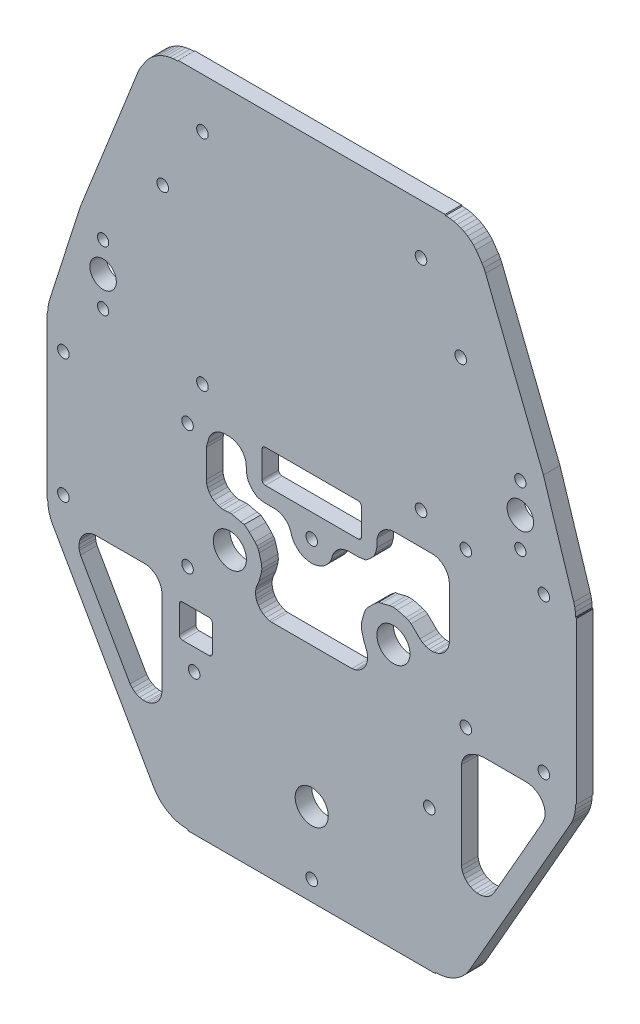
SolidWorks part; units mm, degrees
ref_plane "Plan de face" through (0, 0, 0) normal (1, 0, 0) x (0, 1, 0)
ref_plane "Plan de dessus" through (0, 0, 0) normal (0, 0, 1) x (0, 1, 0)
ref_plane "Plan de droite" through (0, 0, 0) normal (0, 1, 0) x (-1, 0, 0)
sketch "Esquisse1" plane through (0, 0, 0) normal (0, 0, 1) x (0, 1, 0)
  line L0 (0, 0) -> (-150.5414, 0) construction
  line L1 (-100, -80) -> (100, -80)
  line L2 (-100, -80) -> (-100, 80)
  line L3 (-100, 80) -> (100, 80)
  line L5 (-100, -80) -> (100, 80) construction
  line L6 (-100, 80) -> (100, -80) construction
  line L12 (-31, 38.8179) -> (-31, 42.3315) construction
  line L13 (-51, 40) -> (-41, 40)
  line L17 (-51, 40) -> (-51, 30)
  line L18 (-51, 30) -> (-41, 30)
  line L19 (-41, 40) -> (-41, 30)
  line L21 (-31.059, 37.5) -> (-30.571, 37.5) construction
  line L22 (-31, -46.5413) -> (-34.2714, -46.5413) construction
  line L28 (100, 80) -> (100, -80)
  line L30 (2, 15) -> (12, 15)
  line L31 (2, 15) -> (2, -15)
  line L32 (2, -15) -> (12, -15)
  line L33 (12, 15) -> (12, -15)
  circle A0 centre (-75, 0) radius 5
  circle A1 centre (-57.5, 35.5) radius 1.75
  circle A2 centre (-57.5, -35.5) radius 1.75
  circle A3 centre (65, 45) radius 1.75
  circle A4 centre (65, -45) radius 1.75
  circle A5 centre (-31, 37.5) radius 1.75
  circle A6 centre (-31, 75) radius 1.75
  circle A7 centre (6.5, 75) radius 1.75
  circle A8 centre (6.5, 37.5) radius 1.75
  circle A9 centre (-31, -46.5413) radius 1.75
  circle A10 centre (-31, -70.0913) radius 1.75
  circle A11 centre (15.5, -46.5413) radius 1.75
  circle A12 centre (15.5, -70.0913) radius 1.75
  circle A13 centre (-4.9993, 0) radius 1.75
  circle A16 centre (85, 33) radius 1.75
  circle A17 centre (85.0012, -33) radius 1.75
  circle A18 centre (19, 33) radius 1.75
  circle A19 centre (19.0012, -33) radius 1.75
  point P0 (0, 0)
  dimension "D3" = 10
  dimension "D9" = 3.5
  dimension "D10" = 35.5
  dimension "D11" = 17.5
  dimension "D5" = 3.5
  dimension "D6" = 45
  dimension "D7" = 15
  dimension "D16" = 37.5
  dimension "D17" = 37.5
  dimension "D18" = 37.5
  dimension "D19" = 3.5
  dimension "D20" = 3.5
  dimension "D21" = 3.5
  dimension "D22" = 3.5
  dimension "D23" = 10
  dimension "D24" = 5
  dimension "D25" = 3.5
  dimension "D26" = 3.5
  dimension "D27" = 3.5
  dimension "D28" = 3.5
  dimension "D29" = 46.5
  dimension "D30" = 46.5
  dimension "D31" = 23.55
  dimension "D32" = 23.55
  dimension "D35" = 3.5
  dimension "D36" = 3.5
  dimension "D41" = 66
  dimension "D42" = 66
  dimension "D47" = 3.5
  dimension "D48" = 3.5
  dimension "D50" = 66
  dimension "D52" = 33
  dimension "D33" = 14.9988
  dimension "D34" = 3.5
  dimension "D40" = 66
  dimension "D1" = 200
  dimension "D2" = 160
  dimension "D4" = 25
  dimension "D8" = 6.5
  dimension "D12" = 10
  dimension "D13" = 10
  dimension "D14" = 40
  dimension "D15" = 37.5
  dimension "D37" = 15
  dimension "D38" = 15
  dimension "D39" = 10
  dimension "D43" = 102
extrude "Boss.-Extru.1" add sketch "Esquisse1" along normal blind 5
fillet "Congé2" radius 1 8 edges at (-30, -51, 2.5) (-30, -41, 2.5) (-40, -41, 2.5) (-40, -51, 2.5) (15, 2, 2.5) (15, 12, 2.5) (-15, 12, 2.5) (-15, 2, 2.5)
sketch "Esquisse2" plane through (0, 0, 5) normal (0, 0, 1) x (1, 0, 0)
  line L0 (-110, 40) -> (0, 160)
  line L1 (0, 160) -> (110, 40)
  line L2 (110, 40) -> (110, -40)
  line L3 (110, -40) -> (0, -160)
  line L5 (0, -160) -> (-110, -40)
  line L6 (-110, -40) -> (-110, 40)
  line L14 (-573.5804, 598.1671) -> (-698.6982, -488.0825)
  line L15 (-80, 100) -> (-80, -100) construction
  line L16 (80, -100) -> (80, 100) construction
  line L17 (0, 70) -> (0, 33.5097) construction
  line L18 (-698.6982, -488.0825) -> (684.3, -647.3807)
  line L19 (0, 0) -> (-114.7759, 0) construction
  line L20 (684.3, -647.3807) -> (762.9047, 702.4319)
  line L21 (762.9047, 702.4319) -> (-573.5804, 598.1671)
  dimension "D1" = 160
  dimension "D2" = 160
  dimension "D3" = 40
  dimension "D4" = 40
  dimension "D5" = 40
  dimension "D6" = 40
  dimension "D7" = 110
extrude "Enlèv. mat.-Extru.1" cut sketch "Esquisse2" against normal through all
sketch "Esquisse3" plane through (0, 0, 0) normal (0, 0, 1) x (0, 1, 0)
  circle A0 centre (-94.0015, 0.004) radius 1.75
extrude "Trou cuve direction" cut sketch "Esquisse3" along normal through all
sketch "Esquisse4" plane through (0, 0, 5) normal (0, 0, 1) x (1, 0, 0)
  line L0 (-82.024, 47.0385) -> (-45.024, 103.0385)
  line L1 (-45.024, 103.0385) -> (-83.024, 103.0385)
  line L2 (-83.024, 103.0385) -> (-83.024, 47.0385)
  line L3 (-83.024, 47.0385) -> (-82.024, 47.0385)
  line L4 (82.016, 47.0385) -> (45.016, 103.0385)
  line L5 (45.016, 103.0385) -> (83.016, 103.0385)
  line L6 (83.016, 103.0385) -> (83.016, 47.0385)
  line L7 (83.016, 47.0385) -> (82.016, 47.0385)
  circle A0 centre (-63.004, 23.7385) radius 1.7
  circle A1 centre (-63.004, 41.7385) radius 1.7
  circle A2 centre (62.996, 23.7385) radius 1.7
  circle A3 centre (62.996, 41.7385) radius 1.7
  circle A4 centre (-63.004, 32.7385) radius 4
  circle A5 centre (62.996, 32.7385) radius 4
  circle A6 centre (-24.724, -20.2615) radius 5
  circle A7 centre (24.676, -20.2615) radius 5
extrude "Pointe avant, trous berceau et cables" cut sketch "Esquisse4" against normal through all
sketch "Esquisse5" plane through (0, 0, 5) normal (0, 0, 1) x (1, 0, 0)
  line L0 (-80.324, 14.3635) -> (-80.254, 14.1705)
  line L1 (-80.254, 14.1705) -> (-80.076, 14.0675)
  line L2 (-80.076, 14.0675) -> (-79.874, 14.1035)
  line L3 (-79.874, 14.1035) -> (-79.742, 14.2605)
  line L4 (-79.742, 14.2605) -> (-79.662, 15.5635)
  line L5 (-79.662, 15.5635) -> (-79.477, 16.7515)
  line L6 (-79.477, 16.7515) -> (-79.17, 17.9215)
  line L7 (-79.17, 17.9215) -> (-69.975, 46.6925)
  line L8 (-69.975, 46.6925) -> (-52.443, 90.8885)
  line L9 (-52.443, 90.8885) -> (-51.938, 91.9925)
  line L10 (-51.938, 91.9925) -> (-51.322, 93.0375)
  line L11 (-51.322, 93.0375) -> (-49.68, 95.4185)
  line L12 (-49.68, 95.4185) -> (-48.909, 96.2775)
  line L13 (-48.909, 96.2775) -> (-48.056, 97.0555)
  line L14 (-48.056, 97.0555) -> (-47.132, 97.7465)
  line L15 (-47.132, 97.7465) -> (-46.143, 98.3425)
  line L16 (-46.143, 98.3425) -> (-45.101, 98.8385)
  line L17 (-45.101, 98.8385) -> (-44.015, 99.2295)
  line L18 (-44.015, 99.2295) -> (-42.896, 99.5105)
  line L19 (-42.896, 99.5105) -> (-41.754, 99.6815)
  line L20 (-41.754, 99.6815) -> (-40.499, 99.7565)
  line L21 (-40.499, 99.7565) -> (-40.358, 99.8635)
  line L22 (-40.358, 99.8635) -> (-40.302, 100.0305)
  line L23 (-40.302, 100.0305) -> (-40.349, 100.2015)
  line L24 (-40.349, 100.2015) -> (-40.485, 100.3145)
  line L25 (-40.485, 100.3145) -> (-47.056, 100.3385)
  line L26 (-47.056, 100.3385) -> (-47.288, 100.2275)
  line L27 (-47.288, 100.2275) -> (-80.302, 50.2545)
  line L28 (-80.302, 50.2545) -> (-80.324, 14.3635)
  line L29 (-80.324, -72.6885) -> (-80.245, -72.8915)
  line L30 (-80.245, -72.8915) -> (-55.173, -100.2225)
  line L31 (-55.173, -100.2225) -> (-37.575, -100.2615)
  line L32 (-37.575, -100.2615) -> (-37.328, -100.1315)
  line L33 (-37.328, -100.1315) -> (-37.286, -99.8825)
  line L34 (-37.286, -99.8825) -> (-37.476, -99.6785)
  line L35 (-37.476, -99.6785) -> (-39.799, -99.4475)
  line L36 (-39.799, -99.4475) -> (-40.886, -99.1825)
  line L37 (-40.886, -99.1825) -> (-41.942, -98.8155)
  line L38 (-41.942, -98.8155) -> (-42.959, -98.3485)
  line L39 (-42.959, -98.3485) -> (-43.926, -97.7875)
  line L40 (-43.926, -97.7875) -> (-44.835, -97.1365)
  line L41 (-44.835, -97.1365) -> (-45.678, -96.4015)
  line L42 (-45.678, -96.4015) -> (-46.447, -95.5885)
  line L43 (-46.447, -95.5885) -> (-47.135, -94.7065)
  line L44 (-47.135, -94.7065) -> (-47.739, -93.7575)
  line L45 (-47.739, -93.7575) -> (-78.18, -40.4485)
  line L46 (-78.18, -40.4485) -> (-78.73, -39.3585)
  line L47 (-78.73, -39.3585) -> (-79.161, -38.2235)
  line L48 (-79.161, -38.2235) -> (-79.473, -37.0505)
  line L49 (-79.473, -37.0505) -> (-79.661, -35.8525)
  line L50 (-79.661, -35.8525) -> (-79.733, -34.5655)
  line L51 (-79.733, -34.5655) -> (-79.849, -34.3965)
  line L52 (-79.849, -34.3965) -> (-80.017, -34.3405)
  line L53 (-80.017, -34.3405) -> (-80.234, -34.4255)
  line L54 (-80.234, -34.4255) -> (-80.324, -34.6405)
  line L55 (-80.324, -34.6405) -> (-80.324, -72.6885)
  line L56 (54.976, -100.2615) -> (55.197, -100.1645)
  line L57 (55.197, -100.1645) -> (80.256, -72.7975)
  line L58 (80.256, -72.7975) -> (80.276, -34.7105)
  line L59 (80.276, -34.7105) -> (80.224, -34.5415)
  line L60 (80.224, -34.5415) -> (80.086, -34.4305)
  line L61 (80.086, -34.4305) -> (79.853, -34.4365)
  line L62 (79.853, -34.4365) -> (79.694, -34.6075)
  line L63 (79.694, -34.6075) -> (79.613, -35.9225)
  line L64 (79.613, -35.9225) -> (79.425, -37.1205)
  line L65 (79.425, -37.1205) -> (79.113, -38.2935)
  line L66 (79.113, -38.2935) -> (78.682, -39.4285)
  line L67 (78.682, -39.4285) -> (78.132, -40.5185)
  line L68 (78.132, -40.5185) -> (47.731, -93.7575)
  line L69 (47.731, -93.7575) -> (47.127, -94.7065)
  line L70 (47.127, -94.7065) -> (46.439, -95.5885)
  line L71 (46.439, -95.5885) -> (45.67, -96.4015)
  line L72 (45.67, -96.4015) -> (44.827, -97.1365)
  line L73 (44.827, -97.1365) -> (43.918, -97.7875)
  line L74 (43.918, -97.7875) -> (42.951, -98.3485)
  line L75 (42.951, -98.3485) -> (41.934, -98.8155)
  line L76 (41.934, -98.8155) -> (40.878, -99.1825)
  line L77 (40.878, -99.1825) -> (39.791, -99.4475)
  line L78 (39.791, -99.4475) -> (38.685, -99.6075)
  line L79 (38.685, -99.6075) -> (37.496, -99.6705)
  line L80 (37.496, -99.6705) -> (37.329, -99.7795)
  line L81 (37.329, -99.7795) -> (37.267, -99.9685)
  line L82 (37.267, -99.9685) -> (37.358, -100.1765)
  line L83 (37.358, -100.1765) -> (37.567, -100.2615)
  line L84 (37.567, -100.2615) -> (54.976, -100.2615)
  line L85 (80.276, 50.1285) -> (47.232, 100.2275)
  line L86 (47.232, 100.2275) -> (47, 100.3385)
  line L87 (47, 100.3385) -> (40.545, 100.3385)
  line L88 (40.545, 100.3385) -> (40.353, 100.2685)
  line L89 (40.353, 100.2685) -> (40.248, 100.0015)
  line L90 (40.248, 100.0015) -> (40.443, 99.7565)
  line L91 (40.443, 99.7565) -> (41.698, 99.6815)
  line L92 (41.698, 99.6815) -> (42.84, 99.5105)
  line L93 (42.84, 99.5105) -> (43.959, 99.2295)
  line L94 (43.959, 99.2295) -> (45.045, 98.8385)
  line L95 (45.045, 98.8385) -> (46.087, 98.3425)
  line L96 (46.087, 98.3425) -> (47.076, 97.7465)
  line L97 (47.076, 97.7465) -> (48, 97.0555)
  line L98 (48, 97.0555) -> (48.852, 96.2775)
  line L99 (48.852, 96.2775) -> (49.624, 95.4185)
  line L100 (49.624, 95.4185) -> (51.386, 92.8555)
  line L101 (51.386, 92.8555) -> (52.002, 91.8095)
  line L102 (52.002, 91.8095) -> (52.507, 90.7065)
  line L103 (52.507, 90.7065) -> (69.967, 46.6925)
  line L104 (69.967, 46.6925) -> (79.122, 18.0475)
  line L105 (79.122, 18.0475) -> (79.429, 16.8775)
  line L106 (79.429, 16.8775) -> (79.614, 15.6895)
  line L107 (79.614, 15.6895) -> (79.685, 14.4145)
  line L108 (79.685, 14.4145) -> (79.801, 14.2445)
  line L109 (79.801, 14.2445) -> (79.969, 14.1885)
  line L110 (79.969, 14.1885) -> (80.186, 14.2735)
  line L111 (80.186, 14.2735) -> (80.276, 14.4885)
  line L112 (80.276, 14.4885) -> (80.276, 50.1285)
  line L113 (-12.185, -32.8365) -> (12.119, -32.8335)
  line L114 (12.119, -32.8335) -> (13.124, -32.6305)
  line L115 (13.124, -32.6305) -> (13.649, -32.4395)
  line L116 (13.649, -32.4395) -> (14.549, -31.9485)
  line L117 (14.549, -31.9485) -> (14.994, -31.6115)
  line L118 (14.994, -31.6115) -> (15.71, -30.8775)
  line L119 (15.71, -30.8775) -> (16.036, -30.4245)
  line L120 (16.036, -30.4245) -> (16.504, -29.5115)
  line L121 (16.504, -29.5115) -> (16.798, -28.4675)
  line L122 (16.798, -28.4675) -> (16.875, -27.4445)
  line L123 (16.875, -27.4445) -> (16.833, -26.8875)
  line L124 (16.833, -26.8875) -> (16.595, -25.8595)
  line L125 (16.595, -25.8595) -> (15.799, -23.9905)
  line L126 (15.799, -23.9905) -> (15.101, -21.3865)
  line L127 (15.101, -21.3865) -> (14.959, -20.3455)
  line L128 (14.959, -20.3455) -> (15.036, -19.3675)
  line L129 (15.036, -19.3675) -> (15.896, -16.1555)
  line L130 (15.896, -16.1555) -> (16.453, -15.0635)
  line L131 (16.453, -15.0635) -> (17.047, -14.3505)
  line L132 (17.047, -14.3505) -> (18.779, -12.6185)
  line L133 (18.779, -12.6185) -> (20.268, -11.3815)
  line L134 (20.268, -11.3815) -> (20.983, -11.3155)
  line L135 (20.983, -11.3155) -> (23.488, -10.6725)
  line L136 (23.488, -10.6725) -> (24.529, -10.5295)
  line L137 (24.529, -10.5295) -> (25.816, -10.6725)
  line L138 (25.816, -10.6725) -> (28.419, -11.3705)
  line L139 (28.419, -11.3705) -> (29.173, -11.6555)
  line L140 (29.173, -11.6555) -> (30.01, -12.1685)
  line L141 (30.01, -12.1685) -> (32.687, -14.7885)
  line L142 (32.687, -14.7885) -> (33.499, -15.4035)
  line L143 (33.499, -15.4035) -> (34.442, -15.8615)
  line L144 (34.442, -15.8615) -> (35.428, -16.1205)
  line L145 (35.428, -16.1205) -> (36.417, -16.1865)
  line L146 (36.417, -16.1865) -> (36.955, -16.1455)
  line L147 (36.955, -16.1455) -> (38.398, -15.7455)
  line L148 (38.398, -15.7455) -> (38.881, -15.5045)
  line L149 (38.881, -15.5045) -> (39.694, -14.9395)
  line L150 (39.694, -14.9395) -> (40.088, -14.5705)
  line L151 (40.088, -14.5705) -> (40.707, -13.7965)
  line L152 (40.707, -13.7965) -> (41.192, -12.8675)
  line L153 (41.192, -12.8675) -> (41.475, -11.9185)
  line L154 (41.475, -11.9185) -> (41.552, -11.3845)
  line L155 (41.552, -11.3845) -> (41.576, 4.0535)
  line L156 (41.576, 4.0535) -> (41.471, 5.0865)
  line L157 (41.471, 5.0865) -> (41.167, 6.0805)
  line L158 (41.167, 6.0805) -> (40.674, 6.9955)
  line L159 (40.674, 6.9955) -> (40.013, 7.7965)
  line L160 (40.013, 7.7965) -> (39.208, 8.4535)
  line L161 (39.208, 8.4535) -> (38.318, 8.9295)
  line L162 (38.318, 8.9295) -> (37.324, 9.2335)
  line L163 (37.324, 9.2335) -> (36.781, 9.3145)
  line L164 (36.781, 9.3145) -> (24.961, 9.3385)
  line L165 (24.961, 9.3385) -> (23.928, 9.2335)
  line L166 (23.928, 9.2335) -> (22.491, 8.7195)
  line L167 (22.491, 8.7195) -> (22.019, 8.4365)
  line L168 (22.019, 8.4365) -> (21.218, 7.7755)
  line L169 (21.218, 7.7755) -> (20.578, 6.9955)
  line L170 (20.578, 6.9955) -> (20.295, 6.5235)
  line L171 (20.295, 6.5235) -> (19.909, 5.5905)
  line L172 (19.909, 5.5905) -> (19.775, 5.0575)
  line L173 (19.775, 5.0575) -> (19.644, 2.5275)
  line L174 (19.644, 2.5275) -> (19.267, 0.9715)
  line L175 (19.267, 0.9715) -> (18.968, 0.2985)
  line L176 (18.968, 0.2985) -> (18.567, -0.3195)
  line L177 (18.567, -0.3195) -> (17.525, -1.3975)
  line L178 (17.525, -1.3975) -> (16.364, -2.3355)
  line L179 (16.364, -2.3355) -> (14.283, -2.6475)
  line L180 (14.283, -2.6475) -> (10.727, -2.6905)
  line L181 (10.727, -2.6905) -> (9.684, -2.9065)
  line L182 (9.684, -2.9065) -> (8.705, -3.3265)
  line L183 (8.705, -3.3265) -> (7.83, -3.9345)
  line L184 (7.83, -3.9345) -> (7.112, -4.6815)
  line L185 (7.112, -4.6815) -> (6.804, -5.1165)
  line L186 (6.804, -5.1165) -> (6.325, -6.0685)
  line L187 (6.325, -6.0685) -> (5.917, -7.4025)
  line L188 (5.917, -7.4025) -> (5.617, -8.0755)
  line L189 (5.617, -8.0755) -> (5.061, -8.8845)
  line L190 (5.061, -8.8845) -> (4.134, -9.8355)
  line L191 (4.134, -9.8355) -> (3.304, -10.4795)
  line L192 (3.304, -10.4795) -> (2.418, -10.9015)
  line L193 (2.418, -10.9015) -> (0.832, -11.3265)
  line L194 (0.832, -11.3265) -> (-0.147, -11.4035)
  line L195 (-0.147, -11.4035) -> (-1.188, -11.2615)
  line L196 (-1.188, -11.2615) -> (-2.696, -10.8135)
  line L197 (-2.696, -10.8135) -> (-3.558, -10.3455)
  line L198 (-3.558, -10.3455) -> (-4.182, -9.8355)
  line L199 (-4.182, -9.8355) -> (-5.109, -8.8845)
  line L200 (-5.109, -8.8845) -> (-5.665, -8.0755)
  line L201 (-5.665, -8.0755) -> (-5.965, -7.4025)
  line L202 (-5.965, -7.4025) -> (-6.373, -6.0685)
  line L203 (-6.373, -6.0685) -> (-6.852, -5.1165)
  line L204 (-6.852, -5.1165) -> (-7.49, -4.3015)
  line L205 (-7.49, -4.3015) -> (-7.878, -3.9345)
  line L206 (-7.878, -3.9345) -> (-8.753, -3.3265)
  line L207 (-8.753, -3.3265) -> (-9.732, -2.9065)
  line L208 (-9.732, -2.9065) -> (-10.775, -2.6905)
  line L209 (-10.775, -2.6905) -> (-14.331, -2.6475)
  line L210 (-14.331, -2.6475) -> (-16.415, -2.3185)
  line L211 (-16.415, -2.3185) -> (-17.807, -1.1865)
  line L212 (-17.807, -1.1865) -> (-18.759, -0.1205)
  line L213 (-18.759, -0.1205) -> (-19.127, 0.5175)
  line L214 (-19.127, 0.5175) -> (-19.413, 1.2715)
  line L215 (-19.413, 1.2715) -> (-19.692, 2.5275)
  line L216 (-19.692, 2.5275) -> (-19.823, 5.0575)
  line L217 (-19.823, 5.0575) -> (-20.133, 6.0805)
  line L218 (-20.133, 6.0805) -> (-20.609, 6.9705)
  line L219 (-20.609, 6.9705) -> (-20.937, 7.4115)
  line L220 (-20.937, 7.4115) -> (-21.651, 8.1255)
  line L221 (-21.651, 8.1255) -> (-22.092, 8.4535)
  line L222 (-22.092, 8.4535) -> (-23.01, 8.9405)
  line L223 (-23.01, 8.9405) -> (-24.005, 9.2395)
  line L224 (-24.005, 9.2395) -> (-25.009, 9.3385)
  line L225 (-25.009, 9.3385) -> (-26.584, 9.3155)
  line L226 (-26.584, 9.3155) -> (-27.576, 9.1265)
  line L227 (-27.576, 9.1265) -> (-28.08, 8.9515)
  line L228 (-28.08, 8.9515) -> (-28.975, 8.4865)
  line L229 (-28.975, 8.4865) -> (-29.766, 7.8595)
  line L230 (-29.766, 7.8595) -> (-30.424, 7.0935)
  line L231 (-30.424, 7.0935) -> (-30.925, 6.2175)
  line L232 (-30.925, 6.2175) -> (-31.569, 4.1375)
  line L233 (-31.569, 4.1375) -> (-31.793, 3.0845)
  line L234 (-31.793, 3.0845) -> (-31.824, -5.4005)
  line L235 (-31.824, -5.4005) -> (-31.724, -6.4115)
  line L236 (-31.724, -6.4115) -> (-31.443, -7.3585)
  line L237 (-31.443, -7.3585) -> (-30.977, -8.2605)
  line L238 (-30.977, -8.2605) -> (-30.326, -9.0785)
  line L239 (-30.326, -9.0785) -> (-29.552, -9.7365)
  line L240 (-29.552, -9.7365) -> (-28.219, -10.4075)
  line L241 (-28.219, -10.4075) -> (-27.702, -10.5535)
  line L242 (-27.702, -10.5535) -> (-26.723, -10.6825)
  line L243 (-26.723, -10.6825) -> (-24.871, -10.5295)
  line L244 (-24.871, -10.5295) -> (-24.135, -10.5685)
  line L245 (-24.135, -10.5685) -> (-21.474, -11.2345)
  line L246 (-21.474, -11.2345) -> (-20.357, -11.4015)
  line L247 (-20.357, -11.4015) -> (-18.876, -12.6185)
  line L248 (-18.876, -12.6185) -> (-17.144, -14.3505)
  line L249 (-17.144, -14.3505) -> (-16.549, -15.0635)
  line L250 (-16.549, -15.0635) -> (-16.18, -15.7015)
  line L251 (-16.18, -15.7015) -> (-15.86, -16.5735)
  line L252 (-15.86, -16.5735) -> (-15.197, -19.0595)
  line L253 (-15.197, -19.0595) -> (-15.055, -20.3455)
  line L254 (-15.055, -20.3455) -> (-15.197, -21.3865)
  line L255 (-15.197, -21.3865) -> (-15.86, -23.8725)
  line L256 (-15.86, -23.8725) -> (-16.691, -25.8595)
  line L257 (-16.691, -25.8595) -> (-16.836, -26.3675)
  line L258 (-16.836, -26.3675) -> (-16.933, -26.9175)
  line L259 (-16.933, -26.9175) -> (-16.958, -27.9425)
  line L260 (-16.958, -27.9425) -> (-16.778, -28.9825)
  line L261 (-16.778, -28.9825) -> (-16.6, -29.5115)
  line L262 (-16.6, -29.5115) -> (-16.116, -30.4495)
  line L263 (-16.116, -30.4495) -> (-15.456, -31.2725)
  line L264 (-15.456, -31.2725) -> (-14.645, -31.9485)
  line L265 (-14.645, -31.9485) -> (-13.745, -32.4395)
  line L266 (-13.745, -32.4395) -> (-12.737, -32.7535)
  line L267 (-12.737, -32.7535) -> (-12.185, -32.8365)
  line L268 (48.838, -36.9415) -> (47.477, -37.6125)
  line L269 (47.477, -37.6125) -> (47.047, -37.9415)
  line L270 (47.047, -37.9415) -> (46.353, -38.6525)
  line L271 (46.353, -38.6525) -> (46.035, -39.0905)
  line L272 (46.035, -39.0905) -> (45.573, -39.9705)
  line L273 (45.573, -39.9705) -> (45.393, -40.4805)
  line L274 (45.393, -40.4805) -> (45.202, -41.4565)
  line L275 (45.202, -41.4565) -> (45.2, -67.8725)
  line L276 (45.2, -67.8725) -> (45.396, -68.8815)
  line L277 (45.396, -68.8815) -> (45.782, -69.8335)
  line L278 (45.782, -69.8335) -> (46.346, -70.6935)
  line L279 (46.346, -70.6935) -> (47.065, -71.4285)
  line L280 (47.065, -71.4285) -> (47.912, -72.0105)
  line L281 (47.912, -72.0105) -> (48.856, -72.4185)
  line L282 (48.856, -72.4185) -> (49.86, -72.6365)
  line L283 (49.86, -72.6365) -> (50.888, -72.6565)
  line L284 (50.888, -72.6565) -> (51.928, -72.4695)
  line L285 (51.928, -72.4695) -> (53.307, -71.8525)
  line L286 (53.307, -71.8525) -> (54.14, -71.2025)
  line L287 (54.14, -71.2025) -> (55.071, -70.0135)
  line L288 (55.071, -70.0135) -> (69.787, -44.2435)
  line L289 (69.787, -44.2435) -> (70.341, -42.8195)
  line L290 (70.341, -42.8195) -> (70.437, -42.2785)
  line L291 (70.437, -42.2785) -> (70.464, -41.2675)
  line L292 (70.464, -41.2675) -> (70.292, -40.2425)
  line L293 (70.292, -40.2425) -> (70.121, -39.7195)
  line L294 (70.121, -39.7195) -> (69.653, -38.7905)
  line L295 (69.653, -38.7905) -> (69.033, -37.9925)
  line L296 (69.033, -37.9925) -> (68.635, -37.6125)
  line L297 (68.635, -37.6125) -> (67.784, -37.0145)
  line L298 (67.784, -37.0145) -> (66.751, -36.5285)
  line L299 (66.751, -36.5285) -> (65.82, -36.2585)
  line L300 (65.82, -36.2585) -> (64.814, -36.1615)
  line L301 (64.814, -36.1615) -> (51.757, -36.1615)
  line L302 (51.757, -36.1615) -> (50.306, -36.3685)
  line L303 (50.306, -36.3685) -> (48.838, -36.9415)
  line L304 (-50.524, -36.6615) -> (-65.536, -36.6895)
  line L305 (-65.536, -36.6895) -> (-66.539, -36.8915)
  line L306 (-66.539, -36.8915) -> (-67.537, -37.3115)
  line L307 (-67.537, -37.3115) -> (-68.383, -37.8865)
  line L308 (-68.383, -37.8865) -> (-68.771, -38.2435)
  line L309 (-68.771, -38.2435) -> (-69.448, -39.0885)
  line L310 (-69.448, -39.0885) -> (-69.917, -39.9985)
  line L311 (-69.917, -39.9985) -> (-70.088, -40.4965)
  line L312 (-70.088, -40.4965) -> (-70.279, -41.5625)
  line L313 (-70.279, -41.5625) -> (-70.258, -42.5855)
  line L314 (-70.258, -42.5855) -> (-70.17, -43.1055)
  line L315 (-70.17, -43.1055) -> (-69.829, -44.1325)
  line L316 (-69.829, -44.1325) -> (-54.841, -70.3765)
  line L317 (-54.841, -70.3765) -> (-54.188, -71.1315)
  line L318 (-54.188, -71.1315) -> (-53.379, -71.7675)
  line L319 (-53.379, -71.7675) -> (-52.907, -72.0365)
  line L320 (-52.907, -72.0365) -> (-51.948, -72.4075)
  line L321 (-51.948, -72.4075) -> (-50.936, -72.5865)
  line L322 (-50.936, -72.5865) -> (-49.937, -72.5695)
  line L323 (-49.937, -72.5695) -> (-49.401, -72.4815)
  line L324 (-49.401, -72.4815) -> (-48.422, -72.1675)
  line L325 (-48.422, -72.1675) -> (-47.135, -71.3775)
  line L326 (-47.135, -71.3775) -> (-46.735, -71.0085)
  line L327 (-46.735, -71.0085) -> (-46.107, -70.2315)
  line L328 (-46.107, -70.2315) -> (-45.614, -69.2965)
  line L329 (-45.614, -69.2965) -> (-45.327, -68.3405)
  line L330 (-45.327, -68.3405) -> (-45.248, -67.8025)
  line L331 (-45.248, -67.8025) -> (-45.224, -41.9615)
  line L332 (-45.224, -41.9615) -> (-45.329, -40.9135)
  line L333 (-45.329, -40.9135) -> (-45.633, -39.9195)
  line L334 (-45.633, -39.9195) -> (-46.418, -38.6105)
  line L335 (-46.418, -38.6105) -> (-47.173, -37.8555)
  line L336 (-47.173, -37.8555) -> (-48.482, -37.0705)
  line L337 (-48.482, -37.0705) -> (-49.505, -36.7605)
  line L338 (-49.505, -36.7605) -> (-50.524, -36.6615)
extrude "Forme arrondie et allegement" cut sketch "Esquisse5" against normal through all
